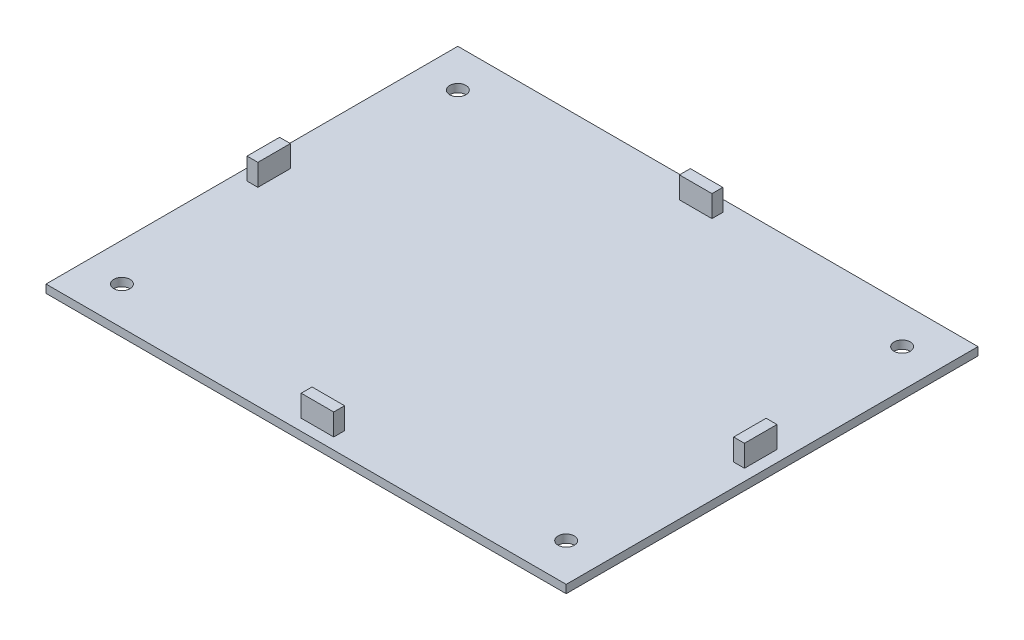
SolidWorks part; units mm, degrees
ref_plane "Front Plane" through (0, 0, 0) normal (0, 0, 1) x (1, 0, 0)
ref_plane "Top Plane" through (0, 0, 0) normal (0, 1, 0) x (1, 0, 0)
ref_plane "Right Plane" through (0, 0, 0) normal (1, 0, 0) x (0, 0, -1)
sketch "Sketch1" plane through (0, 0, 0) normal (0, 1, 0) x (1, 0, 0)
  line L1 (-48, 38) -> (48, 38)
  line L2 (-48, 38) -> (-48, -38)
  line L3 (-48, -38) -> (48, -38)
  line L4 (48, 38) -> (48, -38)
  line L5 (-48, 38) -> (48, -38) construction
  line L6 (-48, -38) -> (48, 38) construction
  point P0 (0, 0)
  dimension "D1" = 96
  dimension "D2" = 76
extrude "Boss-Extrude1" add sketch "Sketch1" along normal blind 1.5
sketch "Sketch2" plane through (0, 1.5, 0) normal (0, 1, 0) x (1, 0, 0)
  line L0 (48, 38) -> (-48, -38) construction
  line L1 (48, 38) -> (-48, 38) construction
  line L2 (-3, 35.9) -> (3, 35.9)
  line L3 (-3, 35.9) -> (-3, 33.9)
  line L4 (-3, 33.9) -> (3, 33.9)
  line L5 (3, 35.9) -> (3, 33.9)
  line L6 (-3, 35.9) -> (3, 33.9) construction
  line L7 (-3, 33.9) -> (3, 35.9) construction
  line L8 (-45.9, 3) -> (-43.9, 3)
  line L9 (-45.9, 3) -> (-45.9, -3)
  line L10 (-45.9, -3) -> (-43.9, -3)
  line L11 (-43.9, 3) -> (-43.9, -3)
  line L12 (-45.9, 3) -> (-43.9, -3) construction
  line L13 (-45.9, -3) -> (-43.9, 3) construction
  line L14 (0, 0) -> (0, 50000) construction
  line L15 (0, 0) -> (-50000, 0) construction
  line L16 (-48, 38) -> (-48, -38) construction
  line L17 (3, -33.9) -> (-3, -33.9)
  line L18 (3, -35.9) -> (-3, -35.9)
  line L19 (-3, -35.9) -> (-3, -33.9)
  line L20 (3, -35.9) -> (3, -33.9)
  line L21 (45.9, -3) -> (43.9, -3)
  line L22 (45.9, -3) -> (45.9, 3)
  line L23 (43.9, -3) -> (43.9, 3)
  line L24 (45.9, 3) -> (43.9, 3)
  point P0 (0, 34.9)
  point P5 (0, 0)
  point P10 (-44.9, 0)
  point P19 (0, 0)
  point P22 (0, 0)
  point P34 (0, 0)
  dimension "D1" = 6
  dimension "D2" = 2.1
  dimension "D3" = 2
  dimension "D4" = 2.1
  dimension "D5" = 2
extrude "Boss-Extrude2" add sketch "Sketch2" along normal blind 4
sketch "Sketch3" plane through (0, 1.5, 0) normal (0, 1, 0) x (1, 0, 0)
  line L0 (-48, -38) -> (48, -38) construction
  line L1 (-48, 38) -> (-48, -38) construction
  circle A0 centre (-41, -31) radius 1.5
  dimension "D1" = 3
  dimension "D2" = 7
  dimension "D3" = 7
extrude "Cut-Extrude1" cut sketch "Sketch3" against normal up to next
mirror "Mirror1" about plane through (0, 0, 0) normal (0, 0, 1) of "Cut-Extrude1"
mirror "Mirror2" about plane through (0, 0, 0) normal (1, 0, 0) of "Mirror1", "Cut-Extrude1"
